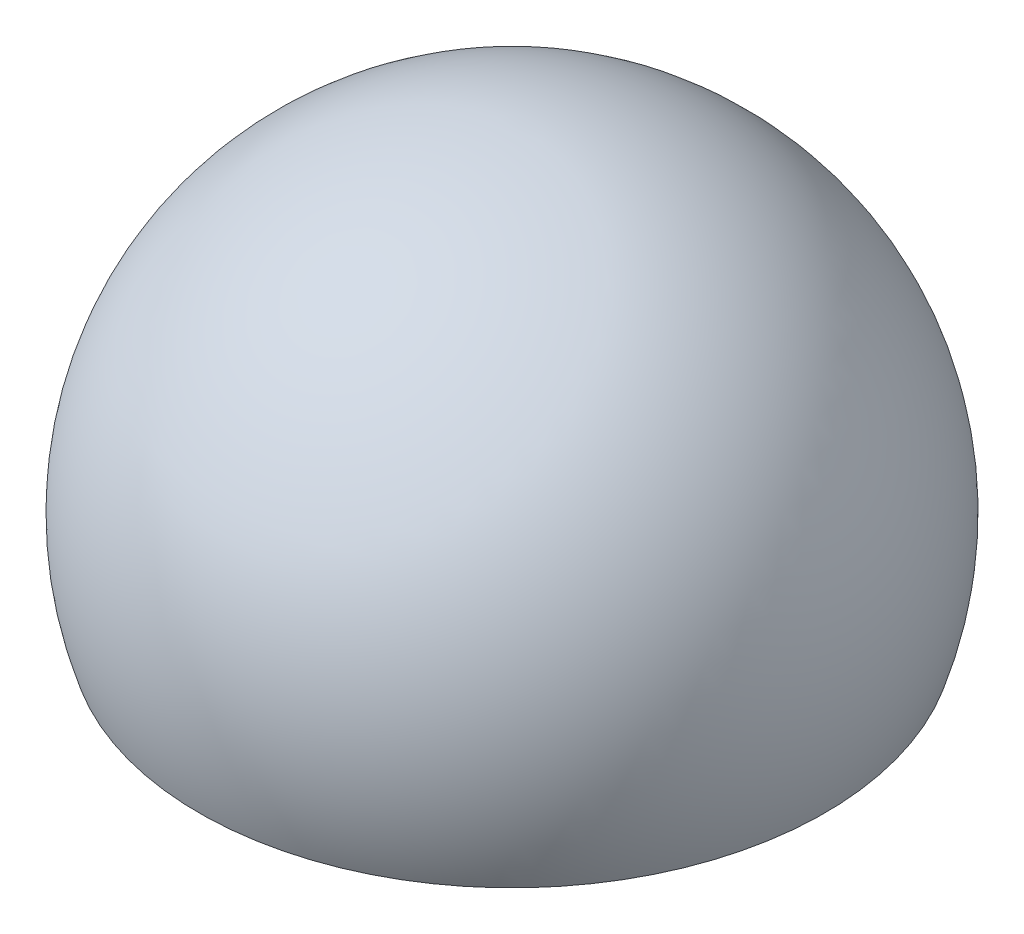
SolidWorks part; units mm, degrees
material "Gray Cast Iron"
ref_plane "Front Plane" through (0, 0, 0) normal (0, 0, 1) x (1, 0, 0)
ref_plane "Top Plane" through (0, 0, 0) normal (0, 1, 0) x (1, 0, 0)
ref_plane "Right Plane" through (0, 0, 0) normal (1, 0, 0) x (0, 0, -1)
sketch "Sketch1" plane through (0, 0, 0) normal (0, 0, 1) x (1, 0, 0)
  line L0 (0, 37.8889) -> (0, -12.1111)
  arc A0 (0, 37.8889) -> (0, -12.1111) centre (0, 12.8889) ccw
  dimension "D1" = 50
revolve "Revolve1" add sketch "Sketch1" angle 360 about L0
sketch "Sketch6" plane through (0, 0, 0) normal (0, 1, 0) x (1, 0, 0)
  line L5 (-30.5698, -28.0643) -> (30.5698, -28.0643)
  line L6 (-30.5698, -28.0643) -> (-30.5698, 28.0643)
  line L7 (-30.5698, 28.0643) -> (30.5698, 28.0643)
  line L8 (30.5698, -28.0643) -> (30.5698, 28.0643)
  line L9 (-30.5698, -28.0643) -> (30.5698, 28.0643) construction
  line L10 (-30.5698, 28.0643) -> (30.5698, -28.0643) construction
  point P0 (0, 0)
extrude "Cut-Extrude7" cut sketch "Sketch6" against normal mid plane 10
sketch "Sketch7" plane through (0, 0, 0) normal (0, 1, 0) x (1, 0, 0)
  line L1 (-2.5, -5) -> (2.5, -5)
  line L2 (-2.5, -5) -> (-2.5, 5)
  line L3 (-2.5, 5) -> (2.5, 5)
  line L4 (2.5, -5) -> (2.5, 5)
  line L5 (-2.5, -5) -> (2.5, 5) construction
  line L6 (-2.5, 5) -> (2.5, -5) construction
  point P0 (0, 0)
extrude "Cut-Extrude8" cut sketch "Sketch7" along normal blind 10
